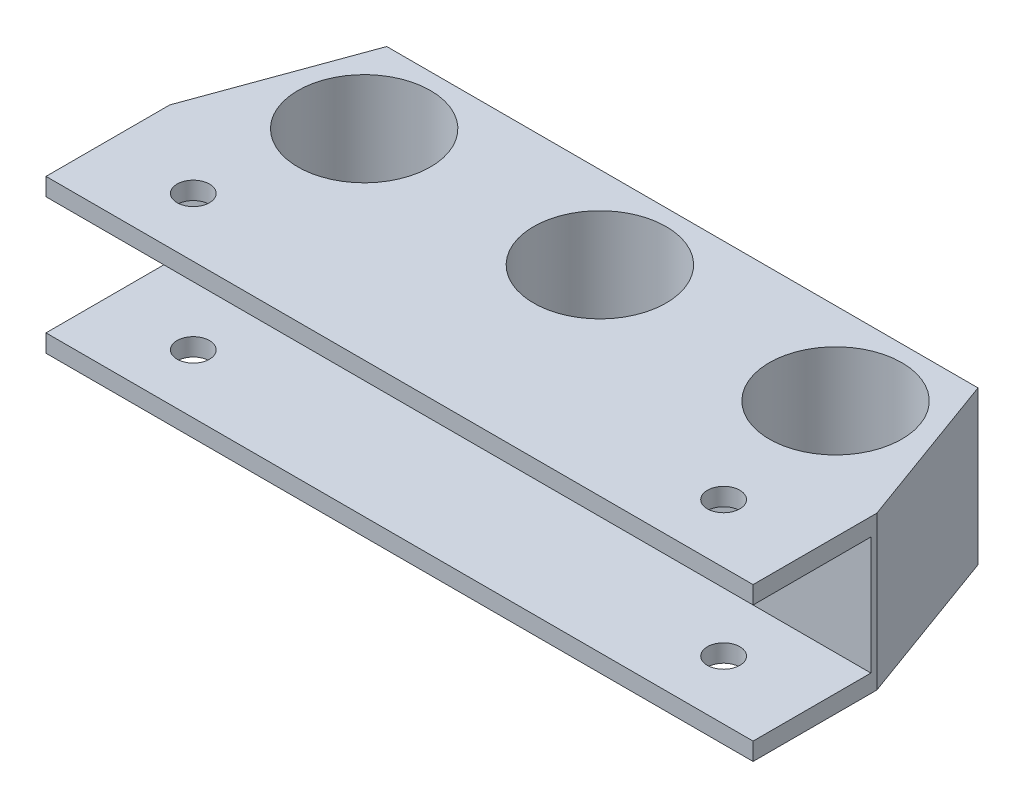
SolidWorks part; units mm, degrees
ref_plane "Спереди" through (0, 0, 0) normal (0, 0, 1) x (1, 0, 0)
ref_plane "Сверху" through (0, 0, 0) normal (0, 1, 0) x (1, 0, 0)
ref_plane "Справа" through (0, 0, 0) normal (1, 0, 0) x (0, 0, -1)
other "Configuration Table"
sketch "Эскиз1" plane through (0, 0, 0) normal (0, 1, 0) x (1, 0, 0)
  line L0 (0, 0) -> (0, 10.5) construction
  line L1 (-60, -10.5) -> (60, -10.5)
  line L2 (-60, -10.5) -> (-60, 10.5)
  line L3 (-60, 10.5) -> (60, 10.5) construction
  line L4 (60, -10.5) -> (60, 10.5)
  line L5 (-60, -10.5) -> (60, 10.5) construction
  line L6 (-60, 10.5) -> (60, -10.5) construction
  line L7 (0, 10.5) -> (0, 64.4132) construction
  line L8 (-60, 10.5) -> (-50.1728, 37.5)
  line L9 (-50.1728, 37.5) -> (0, 37.5)
  line L10 (60, 10.5) -> (50.1728, 37.5)
  line L11 (50.1728, 37.5) -> (0, 37.5)
  circle A0 centre (0, 23.5) radius 11.25
  circle A2 centre (-40, 23.5) radius 11.25
  circle A3 centre (40, 23.5) radius 11.25
  point P0 (0, 0)
  dimension "D3" = 22.5
  dimension "D8" = 14
  dimension "D1" = 120
  dimension "D2" = 21
  dimension "D4" = 13
  dimension "D7" = 40
  dimension "D5" = 70
  dimension "D6" = 2
extrude "Бобышка-Вытянуть1" add sketch "Эскиз1" along normal mid plane 26
sketch "Эскиз2" plane through (-60, 0, 0) normal (-1, 0, 0) x (0, 0, 1)
  line L0 (0, 0) -> (-10.5, 0) construction
  line L1 (0, 0) -> (10.5, 0) construction
  line L3 (-9.5, 10) -> (10.5, 10)
  line L4 (-10.5, -13) -> (10.5, -13)
  line L5 (10.5, -13) -> (10.5, 13)
  line L6 (10.5, 13) -> (-10.5, 13)
  line L7 (-10.5, 13) -> (-10.5, -13)
  line L8 (-10.5, -13) -> (10.5, -13) construction
  line L9 (10.5, -13) -> (10.5, 13) construction
  line L10 (10.5, 13) -> (-10.5, 13) construction
  line L11 (-10.5, 13) -> (-10.5, -13) construction
  line L12 (-9.5, 10) -> (-9.5, -10)
  line L13 (-9.5, -10) -> (10.5, -10)
  line L14 (10.5, 10) -> (10.5, -10)
  line L15 (-9.5, 10) -> (10.5, -10) construction
  line L16 (-9.5, -10) -> (10.5, 10) construction
  point P6 (0.5, 0)
  point P9 (0.5, 0)
  dimension "D2" = 10
  dimension "D1" = 0
extrude "Вырез-Вытянуть1" cut sketch "Эскиз2" against normal through all
sketch "Sketch1" plane through (0, 10, 0) normal (0, -1, 0) x (1, 0, 0)
  line L0 (45, 10.5) -> (45, -9.5) construction
  line L1 (60, 10.5) -> (-60, 10.5) construction
  line L2 (60, -9.5) -> (-60, -9.5) construction
  line L3 (-45, 10.5) -> (-45, -9.5) construction
  circle A0 centre (45, 0.5) radius 2.75
  circle A1 centre (-45, 0.5) radius 2.75
  dimension "D2" = 5.5
  dimension "D4" = 5.5
  dimension "D1" = 15
  dimension "D3" = 15
extrude "Cut-Extrude1" cut sketch "Sketch1" against normal through all both and the other way through all
equation "\"BearingHole\"= 22.5мм"
